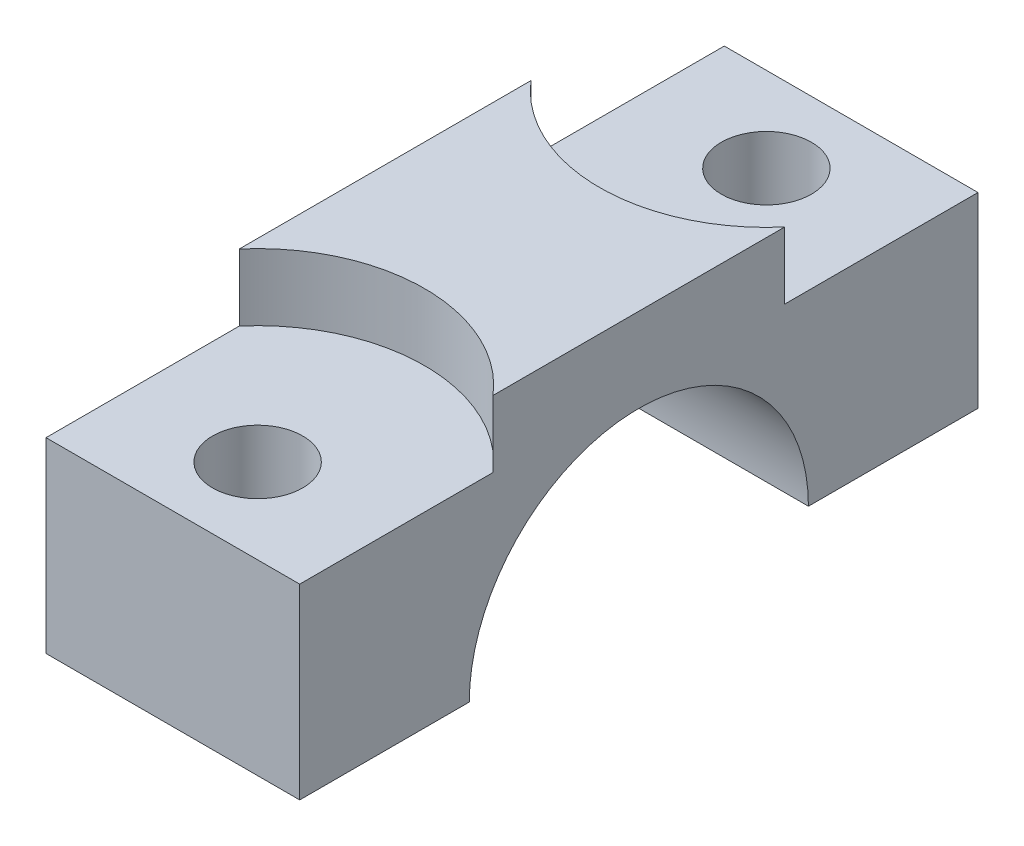
SolidWorks part; units mm, degrees
ref_plane "Front Plane" through (0, 0, 0) normal (0, 0, 1) x (1, 0, 0)
ref_plane "Top Plane" through (0, 0, 0) normal (0, 1, 0) x (1, 0, 0)
ref_plane "Right Plane" through (0, 0, 0) normal (1, 0, 0) x (0, 0, -1)
sketch "Sketch1" plane through (0, 0, 0) normal (1, 0, 0) x (0, 0, -1)
  line L0 (12.7, 0) -> (25.4, 0)
  line L1 (-25.4, 19) -> (25.4, 19)
  line L2 (-25.4, 19) -> (-25.4, 0)
  line L3 (-25.4, 0) -> (-12.7, 0)
  line L4 (25.4, 19) -> (25.4, 0)
  arc A0 (12.7, 0) -> (-12.7, 0) centre (0, 0) ccw
  point P10 (0, 19)
  dimension "D3" = 12.7
  dimension "D1" = 50.8
  dimension "D2" = 19
  dimension "D4" = 0
extrude "Boss-Extrude1" add sketch "Sketch1" along normal mid plane 19
sketch "Sketch2" plane through (0, 0, 0) normal (0, -1, 0) x (1, 0, 0)
  line L0 (-9.5, 19.05) -> (9.5, 19.05) construction
  line L1 (-9.5, 25.4) -> (-9.5, 12.7) construction
  line L2 (9.5, 25.4) -> (9.5, 12.7) construction
  line L3 (-9.5, -19.05) -> (9.5, -19.05) construction
  line L4 (-9.5, -12.7) -> (-9.5, -25.4) construction
  line L5 (9.5, -12.7) -> (9.5, -25.4) construction
  point P12 (0, 19.05)
  point P13 (0, -19.05)
hole_wizard "CBORE for M12 Hex Head Cap Screw2" positions "Sketch5" profile "Sketch6" counterbore size "M12" standard "ISO" end condition through all
sketch "Sketch5" plane through (0, 19, 0) normal (0, 1, 0) x (1, 0, 0)
  point P0 (0, 19.05)
  point P3 (0, -19.05)
sketch "Sketch6" plane through (0, 19, -19.05) normal (1, 0, 0) x (0, 0, 1)
  line L0 (0, 0) -> (0, 19)
  line L1 (0, 19) -> (3.375, 19)
  line L3 (3.375, 19) -> (3.375, 5)
  line L4 (3.375, 5) -> (12.5, 5)
  line L5 (12.5, 5) -> (12.5, 0)
  line L7 (12.5, 0) -> (0, 0)
  line L11 (0, -6.35) -> (0, 107.95) construction
  dimension "Thru Hole Dia." = 6.75
  dimension "Thru Hole Depth" = 19
  dimension "C'Bore Dia." = 25
  dimension "C'Bore Depth" = 5
